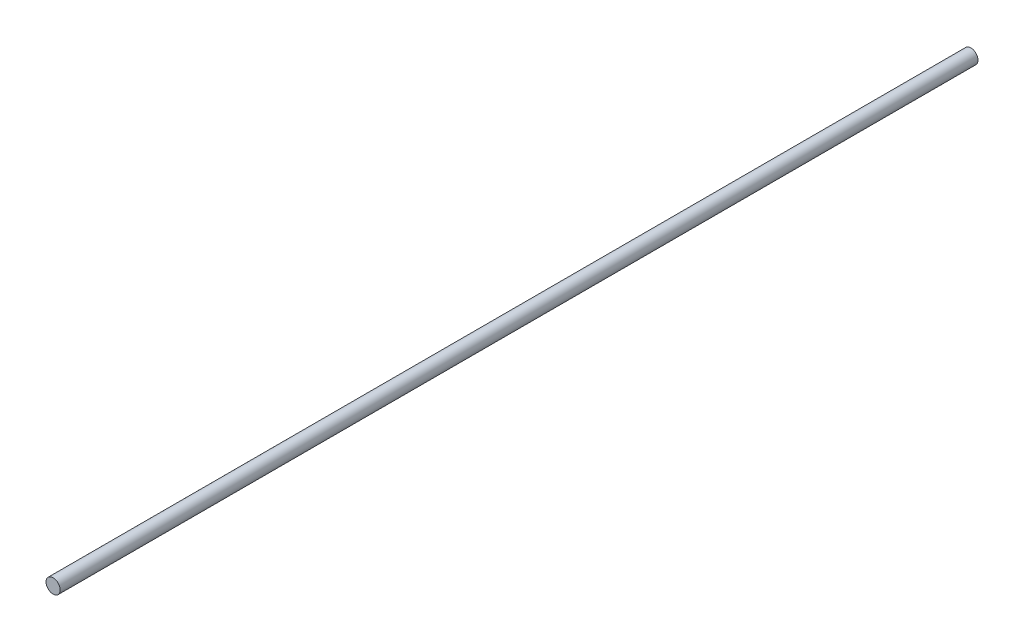
SolidWorks part; units mm, degrees
ref_plane "Front Plane" through (0, 0, 0) normal (0, 0, 1) x (1, 0, 0)
ref_plane "Top Plane" through (0, 0, 0) normal (0, 1, 0) x (1, 0, 0)
ref_plane "Right Plane" through (0, 0, 0) normal (1, 0, 0) x (0, 0, -1)
sketch "Sketch1" plane through (0, 0, 0) normal (0, 0, 1) x (1, 0, 0)
  circle A0 centre (0, 0) radius 2.4
  dimension "D1" = 4.8
extrude "Boss-Extrude1" add sketch "Sketch1" along normal blind 310 contours A0
